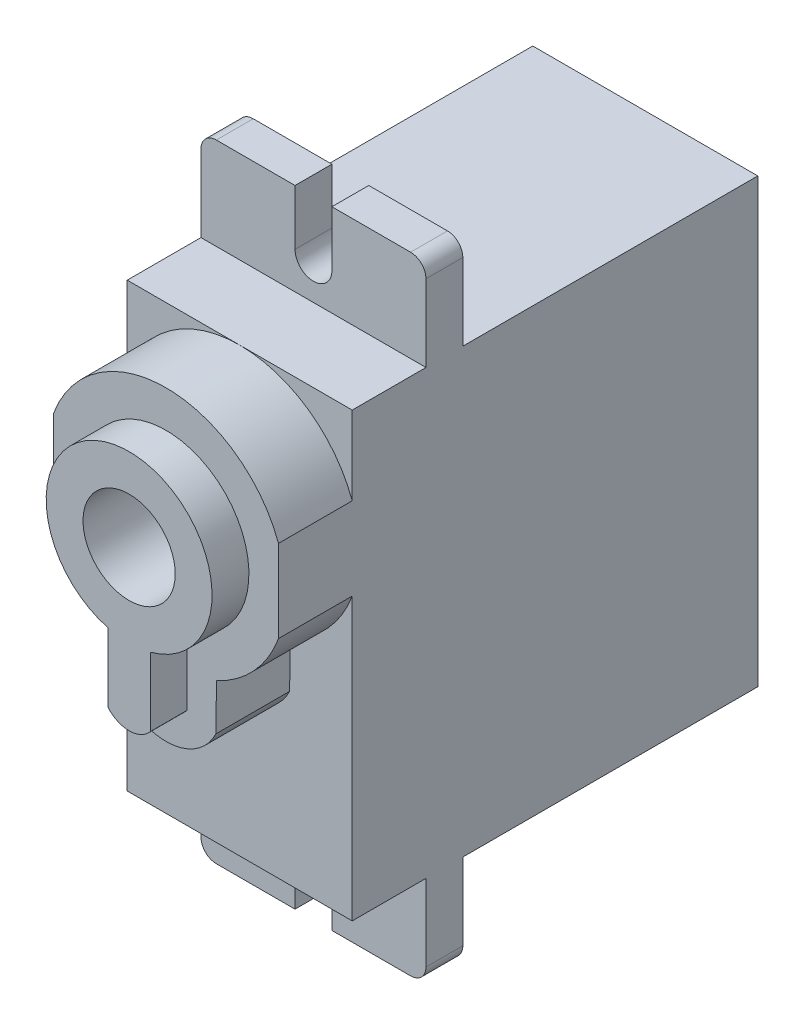
SolidWorks part; units mm, degrees
ref_plane "Plan de face" through (0, 0, 0) normal (0, 0, 1) x (1, 0, 0)
ref_plane "Plan de dessus" through (0, 0, 0) normal (0, 1, 0) x (1, 0, 0)
ref_plane "Plan de droite" through (0, 0, 0) normal (1, 0, 0) x (0, 0, -1)
sketch "Esquisse1" plane through (0, 0, 0) normal (0, 0, 1) x (1, 0, 0)
  line L0 (0, 27.2115) -> (0, -28.8709) construction
  line L1 (-7.3237, 20.4) -> (-1.2, 20.4)
  line L2 (7.3237, 20.4) -> (7.3237, -20.4)
  line L4 (-7.3237, 20.4) -> (-7.3237, -20.4)
  line L5 (1.2, 20.4) -> (1.2, 16.8)
  line L6 (-18.684, 0) -> (13.3011, 0) construction
  line L7 (-1.2, 20.4) -> (-1.2, 16.8)
  line L8 (-7.3237, -20.4) -> (-1.2, -20.4)
  line L11 (1.2, -20.4) -> (7.3237, -20.4)
  line L12 (1.2, 20.4) -> (7.3237, 20.4)
  line L13 (-1.2, -20.4) -> (-1.2, -16.8)
  line L14 (1.2, -20.4) -> (1.2, -16.8)
  arc A2 (-1.2, 16.8) -> (1.2, 16.8) centre (0, 16.8) ccw
  arc A3 (-1.2, -16.8) -> (1.2, -16.8) centre (0, -16.8) cw
  point P9 (0, -21.5802)
  point P10 (0, 19.2198)
  point P14 (0, 16.8)
  dimension "D2" = 2.4
  dimension "D1" = 40.8
  dimension "D3" = 2.4
  dimension "D4" = 3.6
extrude "Boss.-Extru.2" add sketch "Esquisse1" along normal blind 2.4
sketch "Esquisse3" plane through (0, 0, 2.4) normal (0, 0, 1) x (1, 0, 0)
  line L0 (-11.4165, 0) -> (11.7642, 0) construction
  line L1 (-7.3237, 14.4) -> (7.3237, 14.4)
  line L2 (-7.3237, 20.4) -> (-7.3237, -20.4) construction
  line L3 (7.3237, -20.4) -> (7.3237, 20.4) construction
  line L4 (-7.3237, -14.4) -> (7.3237, -14.4)
  line L5 (-7.3237, 14.4) -> (-7.3237, -14.4)
  line L6 (7.3237, 14.4) -> (7.3237, -14.4)
  dimension "D1" = 28.8
extrude "Boss.-Extru.3" add sketch "Esquisse3" along normal blind 4.8
sketch "Esquisse4" plane through (0, 0, 7.2) normal (0, 0, 1) x (1, 0, 0)
  line L0 (0, 19.7303) -> (0, -23.2811) construction
  line L1 (-1.3825, 1.38) -> (-1.3825, -3.0967)
  line L2 (-7.3237, 14.4) -> (7.3237, 14.4)
  line L3 (1.3825, 1.38) -> (1.3825, -3.0967)
  line L4 (-3.2862, -0.474) -> (-3.2862, -3.414)
  line L5 (3.2862, -0.474) -> (3.2491, -3.4943)
  line L6 (-7.3608, 9.1804) -> (-7.3237, 3.9161)
  line L7 (-7.3237, 14.4) -> (-7.3237, -14.4) construction
  line L8 (7.3237, 9.2839) -> (7.3237, 3.9161)
  line L9 (7.3237, -14.4) -> (7.3237, 14.4) construction
  arc A0 (3.2862, -0.474) -> (7.3237, 3.9161) centre (0, 6.6) ccw
  arc A1 (-3.2862, -3.414) -> (3.2491, -3.4943) centre (0, -1.944) ccw
  circle A2 centre (0, 6.6) radius 3
  arc A3 (1.3825, 1.38) -> (-1.3825, 1.38) centre (0, 6.6) ccw
  arc A4 (-1.3825, -3.0967) -> (1.3825, -3.0967) centre (0, -1.944) ccw
  arc A5 (-7.3237, 3.9161) -> (-3.2862, -0.474) centre (0, 6.6) ccw
  arc A6 (7.3237, 9.2839) -> (-7.3608, 9.1804) centre (0, 6.6) ccw
  line M16 (-7.3237, 14.4) -> (-7.3237, -14.4)
  line M18 (7.3237, -14.4) -> (7.3237, 14.4)
  dimension "D2" = 15.6
  dimension "D3" = 7.2
  dimension "D5" = 6
  dimension "D6" = 10.8
  dimension "D7" = 3.6
  dimension "D1" = 8.544
  dimension "D4" = 16.344
sketch "Esquisse6" plane through (0, 0, 7.2) normal (0, 0, 1) x (1, 0, 0)
extrude "Boss.-Extru.4" add sketch "Esquisse4" along normal blind 4.8 contours L0 A6 A5 L4 A1 A4 L1 A3 M16 | A6 L0 A3 L3 A4 A1 L5 A0 M18
sketch "Esquisse7" plane through (0, 0, 7.2) normal (0, 0, 1) x (1, 0, 0)
  line L0 (-1.3825, 1.38) -> (-1.3825, -3.0967)
  line L1 (1.3825, 1.38) -> (1.3825, -3.0967)
  arc A0 (-1.3825, -3.0967) -> (1.3825, -3.0967) centre (0, -1.944) ccw
  arc A1 (1.3825, 1.38) -> (-1.3825, 1.38) centre (0, 6.6) ccw
  circle A2 centre (0, 6.6) radius 3
  dimension "D1" = 6
extrude "Boss.-Extru.5" add sketch "Esquisse7" along normal blind 7.2
sketch "Esquisse8" plane through (0, 0, 7.2) normal (0, 0, 1) x (1, 0, 0)
  circle A0 centre (0, 6.6) radius 3
extrude "Enlèv. mat.-Extru.1" cut sketch "Esquisse8" against normal blind 4.8
sketch "Esquisse9" plane through (0, 0, 0) normal (0, 0, -1) x (-1, 0, 0)
  line L0 (-14.1697, 0) -> (12.8967, 0) construction
  line L1 (-7.3237, 14.4) -> (7.3237, 14.4)
  line L2 (-7.3237, -20.4) -> (-7.3237, 20.4) construction
  line L3 (7.3237, 20.4) -> (7.3237, -20.4) construction
  line L4 (-7.3237, -14.4) -> (7.3237, -14.4)
  line L5 (-7.3237, 14.4) -> (-7.3237, -14.4)
  line L6 (7.3237, 14.4) -> (7.3237, -14.4)
  dimension "D1" = 28.8
extrude "Boss.-Extru.6" add sketch "Esquisse9" along normal blind 19.2
fillet "Congé1" radius 1 4 edges at (-7.3237, -20.4, 1.2) (7.3237, -20.4, 1.2) (7.3237, 20.4, 1.2) (-7.3237, 20.4, 1.2)
